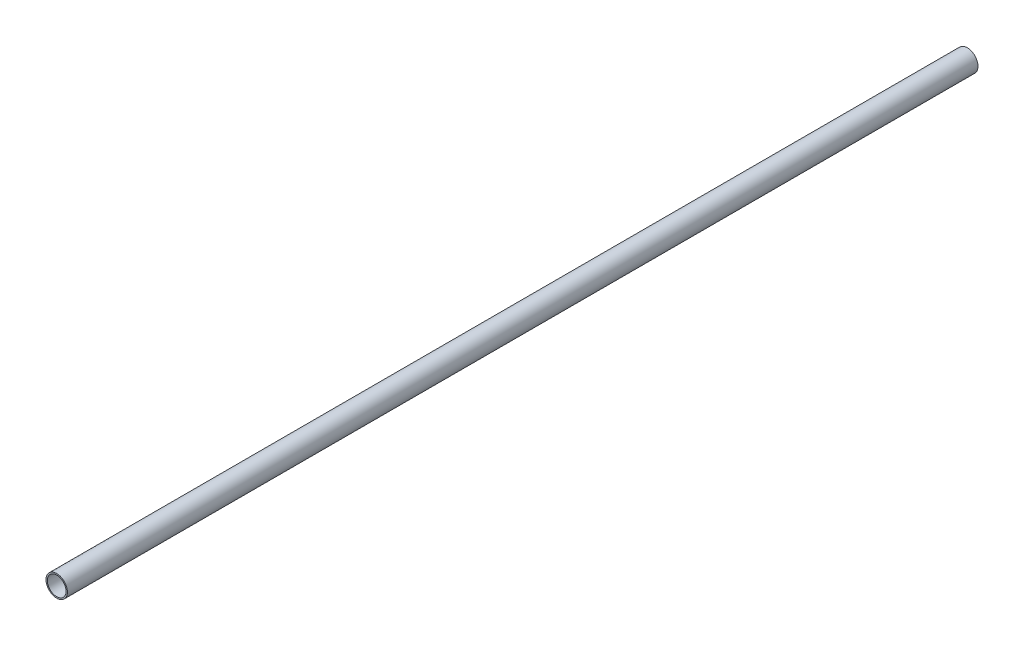
SolidWorks part; units mm, degrees
material "CarbonFiber"
ref_plane "Спереди" through (0, 0, 0) normal (0, 0, 1) x (1, 0, 0)
ref_plane "Сверху" through (0, 0, 0) normal (0, 1, 0) x (1, 0, 0)
ref_plane "Справа" through (0, 0, 0) normal (1, 0, 0) x (0, 0, -1)
sketch "Эскиз1" plane through (0, 0, 0) normal (0, 0, 1) x (1, 0, 0)
  circle A1 centre (0, 0) radius 8
  circle A2 centre (0, 0) radius 7
  dimension "D1" = 16
  dimension "D2" = 1
extrude "Бобышка-Вытянуть1" add sketch "Эскиз1" along normal mid plane 680
equation "\"DTailTube\"= 16mm'Диаметр трубки хвостового оперения"
equation "\"FusLenght\"= 700mm"
equation "\"DMotor\"= 35.2mm"
equation "\"MotorArm\"= 320mm"
equation "\"DFus\"= 150mm"
equation "\"DFusTube\"= 30mm'Диаметр трубки внутри фюзеляжа"
equation "\"FusTubeHeight\"= 40mm"
equation "\"FusCentralPartLenght\"= 410mm"
equation "\"FusNoseLenght\"= 150mm"
equation "\"WingOffset\"= 1mm'Расстояние от внутренней поверхности фюзеляжа до профиля крыла по вертикали"
equation "\"EllipseRatio\"= 0.95'Центральная часть фюзеляжа - эллипс. Этот параметр - отношение длин осей эллипса"
equation "\"FrameOffset\"= 0.6mm"
equation "\"DThreadedInsert\"= 3mm'Внешний диамер резьбовых втулок"
equation "\"CenterSectionLenght\"= 140mm'Длина центроплана"
equation "\"b\"= 1700mm'Размах"
equation "\"cwr\"= 236mm'Корневая хорда крыла"
equation "\"TR\"= 0.75'Сужение крыла"
equation "\"cwt\"= \"TR\" * \"cwr\"'Концевая хорда крыла"
equation "\"DWingMainSpar\"= 16mm'Диаметр главного лонжерона крыла"
equation "\"DWingSecondSpar\"= 8mm'Диаметр второго лонжерона крыла"
equation "\"WingSparsDistance\"= 80mm'Расстояния между отверстиями по лонжерон крыла"
equation "\"c\"= 210mm'САХ крыла"
equation "\"FusTubeLenght\"= \"FusLenght\"-90mm'Длина трубки фюзеляжа"
equation "\"bt\"=291mm'Высота лопатки хвоста"
equation "\"D1@Эскиз1\"=\"DTailTube\""
equation "\"TailTubeLenght\"=680mm'Длина хвостовой балки"
equation "\"D1@Бобышка-Вытянуть1\"=\"TailTubeLenght\""
equation "\"ct\"=182mm'Корневая хорда хвоста"
equation "\"lambda_t\"=0.3'Доля хвоста, занатая рулем высоты"
equation "\"DStringer\"=6mm'Диаметр стрингеров"
equation "\"TailConnectorBaseLenght\"=20mm'Высота основания конектора хвоста"
equation "\"CargoHolderHoleDistance\"=30mm'Расстояние между крепежными отверстиями для держателя груза"
equation "\"FuselageThickness\"=1.2mm'Толщина фюзеляжа"
equation "\"DTailSpar\"=6mm'Диаметр лонжерона хвостового оперения"
equation "\"TailSparDistance\"=40mm'Расстояние между лонжеронами хвостового оперения"
equation "\"CrossSectionWidth\"=15mm'Ширина кольцевой части шпангоута"
equation "\"ThreadedInsertLenght\"=4mm'Длина резьбовых втулок"
equation "\"ThreadedInsertThread\"=2mm'Диаметр резьбы втулки"
equation "\"HingeLenght\"=30mm'Длина отверстия под шарнир хвостового оперения"
equation "\"HingeWidth\"=2.4mm'Высота отверстия под шарнир ХО"
equation "\"HingeDepth\"=15mm'Глубина отверстия под шарнир ХО"
equation "\"DMagnet\"=3mm'Диаметр магнитов"
equation "\"MagnetHeight\"=2mm'Высота магнитов"
equation "\"PlywoodThickness\"=2.9mm'Толщина фанеры"
